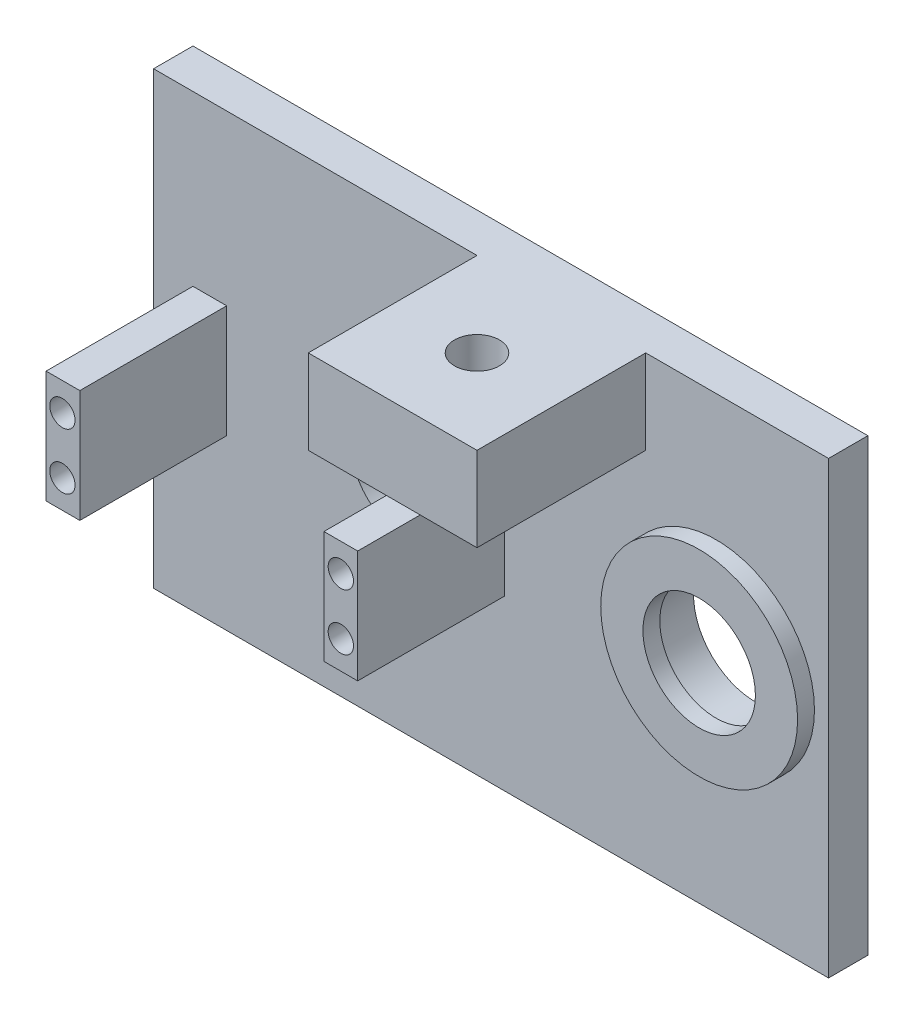
SolidWorks part; units mm, degrees
material "Nylon 101"
ref_plane "Front Plane" through (0, 0, 0) normal (0, 0, 1) x (1, 0, 0)
ref_plane "Top Plane" through (0, 0, 0) normal (0, 1, 0) x (1, 0, 0)
ref_plane "Right Plane" through (0, 0, 0) normal (1, 0, 0) x (0, 0, -1)
sketch "Sketch1" plane through (0, 0, 0) normal (0, 0, 1) x (1, 0, 0)
  line L1 (-60, -40) -> (60, -40)
  line L2 (-60, -40) -> (-60, 40)
  line L3 (-60, 40) -> (60, 40)
  line L4 (60, -40) -> (60, 40)
  line L5 (-60, -40) -> (60, 40) construction
  line L6 (-60, 40) -> (60, -40) construction
  circle A0 centre (-15, 0) radius 10
  circle A1 centre (40, 0) radius 11
  point P0 (0, 0)
  dimension "D1" = 20
  dimension "D2" = 22
  dimension "D3" = 15
  dimension "D4" = 40
  dimension "D5" = 120
  dimension "D6" = 80
extrude "Boss-Extrude1" add sketch "Sketch1" along normal mid plane 7
sketch "Sketch2" plane through (0, 0, 3.5) normal (0, 0, 1) x (1, 0, 0)
  circle A0 centre (40, 0) radius 11 construction
  circle A1 centre (40, 0) radius 11
  circle A2 centre (40, 0) radius 10
  circle A3 centre (40, 0) radius 17.5
  circle M6 centre (40, 0) radius 11
  dimension "D1" = 20
  dimension "D2" = 35
extrude "Boss-Extrude2" add sketch "Sketch2" along normal blind 3 contours A3 M6 | A2 M6 | A1
sketch "Sketch3" plane through (0, 0, 3.5) normal (0, 0, 1) x (1, 0, 0)
  line L0 (-15, 0) -> (-15, 10) construction
  line L1 (-53, 10) -> (-47, 10)
  line L2 (-53, 10) -> (-53, -10)
  line L3 (-53, -10) -> (-47, -10)
  line L4 (-47, 10) -> (-47, -10)
  line L5 (-3.6, 10) -> (2.4, 10)
  line L6 (-3.6, 10) -> (-3.6, -10)
  line L7 (-3.6, -10) -> (2.4, -10)
  line L8 (2.4, 10) -> (2.4, -10)
  line L9 (-60, 40) -> (-60, -40) construction
  line L10 (-15, 0) -> (-25, 0) construction
  circle A0 centre (-50.1, 5) radius 2.25
  circle A1 centre (-50.1, -5) radius 2.25
  circle A2 centre (-0.6, 5) radius 2.25
  circle A3 centre (-0.6, -5) radius 2.25
  circle A4 centre (-15, 0) radius 10 construction
  circle A5 centre (-15, 0) radius 10
  dimension "D1" = 4.5
  dimension "D2" = 49.5
  dimension "D3" = 9.9
  dimension "D4" = 10
  dimension "D5" = 7
  dimension "D6" = 6
  dimension "D7" = 20
  dimension "D8" = 5
  dimension "D9" = 6
  dimension "D10" = 20
  dimension "D11" = 3
extrude "Boss-Extrude3" add sketch "Sketch3" along normal blind 26.11 contours L4 L1 L2 L3 A1 A0 | L8 L5 L6 L7 A3 A2
sketch "Sketch4" plane through (0, 0, 3.5) normal (0, 0, 1) x (1, 0, 0)
  circle A0 centre (-50.1, 5) radius 2.25 construction
  circle A1 centre (-50.1, -5) radius 2.25 construction
  circle A2 centre (-0.6, 5) radius 2.25 construction
  circle A3 centre (-0.6, -5) radius 2.25 construction
  circle A4 centre (-50.1, 5) radius 2.25
  circle A5 centre (-50.1, -5) radius 2.25
  circle A6 centre (-0.6, 5) radius 2.25
  circle A7 centre (-0.6, -5) radius 2.25
extrude "Cut-Extrude1" cut sketch "Sketch4" against normal blind 26.11
sketch "Sketch5" plane through (0, 0, 3.5) normal (0, 0, 1) x (1, 0, 0)
  line L0 (60, 40) -> (-60, 40) construction
  line L1 (-2.5, 40) -> (27.5, 40)
  line L2 (-2.5, 40) -> (-2.5, 25)
  line L3 (-2.5, 25) -> (27.5, 25)
  line L4 (27.5, 40) -> (27.5, 25)
  dimension "D1" = 30
  dimension "D2" = 27.5
  dimension "D3" = 15
extrude "Boss-Extrude4" add sketch "Sketch5" along normal blind 30
sketch "Sketch6" plane through (0, 40, 0) normal (0, 1, 0) x (1, 0, 0)
  line L0 (27.5, -33.5) -> (-2.5, -33.5) construction
  line L1 (-2.5, -33.5) -> (-2.5, -3.5) construction
  circle A0 centre (12.5, -18.5) radius 4
  dimension "D2" = 8
  dimension "D1" = 15
  dimension "D3" = 15
extrude "Cut-Extrude2" cut sketch "Sketch6" against normal blind 29
